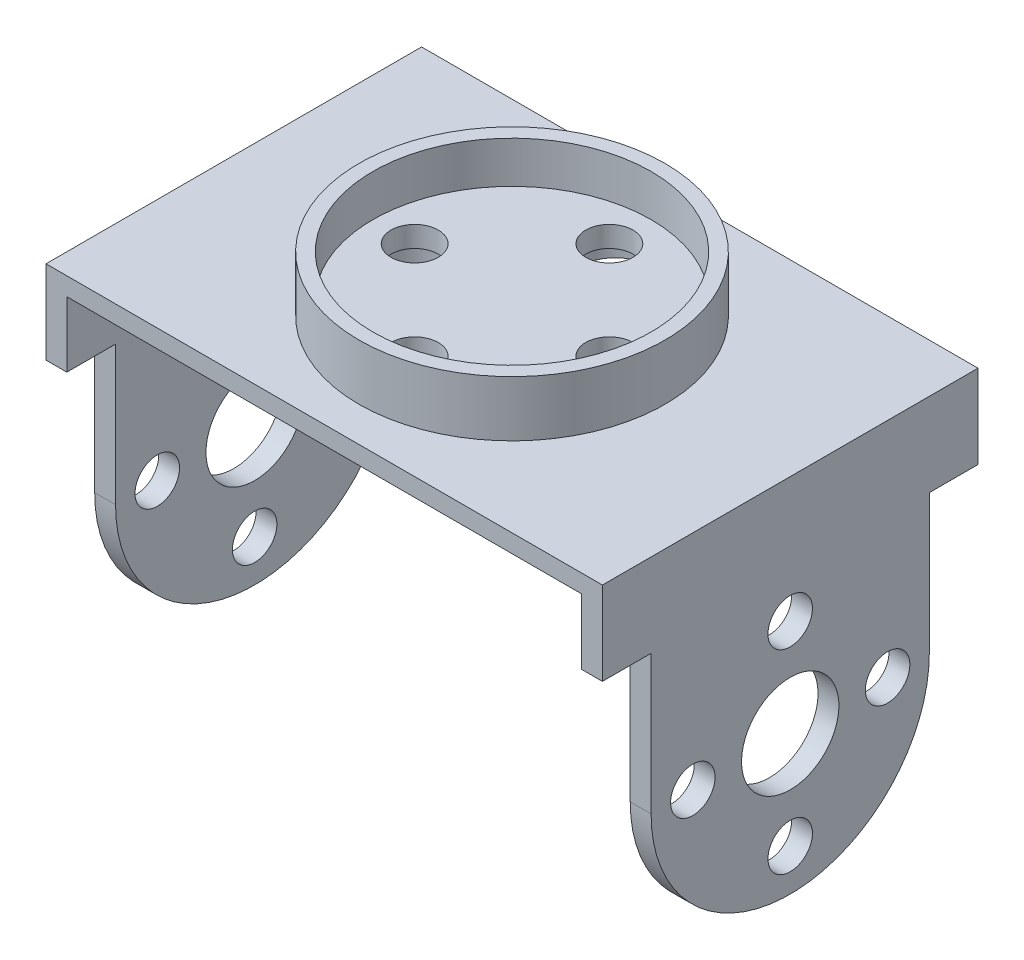
SolidWorks part; units mm, degrees
ref_plane "前视基准面" through (0, 0, 0) normal (0, 0, 1) x (1, 0, 0)
ref_plane "上视基准面" through (0, 0, 0) normal (0, 1, 0) x (1, 0, 0)
ref_plane "右视基准面" through (0, 0, 0) normal (1, 0, 0) x (0, 0, -1)
other "Configuration Table"
sketch "草图1" plane through (0, 0, 0) normal (0, 0, 1) x (1, 0, 0)
  line L1 (0, 0) -> (40, 0)
  line L2 (0, 0) -> (0, 28)
  line L3 (0, 28) -> (40, 28)
  line L4 (40, 0) -> (40, 28)
  dimension "D1" = 40
  dimension "D2" = 28
extrude "凸台-拉伸1" add sketch "草图1" along normal blind 27
sketch "草图2" plane through (0, 0, 0) normal (0, -1, 0) x (1, 0, 0)
  line L0 (20, 0) -> (20, 50000) construction
  line L1 (0, 0) -> (40, 0) construction
  line L2 (0, 27) -> (40, 27) construction
  line L3 (1.5, 0) -> (38.5, 0)
  line L4 (1.5, 0) -> (1.5, 27)
  line L5 (1.5, 27) -> (38.5, 27)
  line L6 (38.5, 0) -> (38.5, 27)
  point P4 (20, 0)
  point P9 (20, 0)
  dimension "D1" = 37
extrude "切除-拉伸1" cut sketch "草图2" against normal offset from surface (25 mm away) 3 up to face at (20, 28, 13.5)
sketch "草图3" plane through (0, 0, 0) normal (-1, 0, 0) x (0, 0, 1)
  line L0 (13.5, 0) -> (13.5, -50000) construction
  line L1 (27, 0) -> (0, 0) construction
  circle A0 centre (13.5, 12) radius 7 construction
  circle A1 centre (13.5, 5) radius 1.6
  circle A2 centre (13.5, 12) radius 3.5
  circle A3 centre (6.5, 12) radius 1.6
  circle A4 centre (20.5, 12) radius 1.6
  circle A5 centre (13.5, 19) radius 1.6
  point P4 (13.5, 0)
  dimension "D1" = 14
  dimension "D2" = 3.2
  dimension "D3" = 7
  dimension "D4" = 3.2
  dimension "D5" = 3.2
  dimension "D6" = 3.2
  dimension "D7" = 12
extrude "切除-拉伸2" cut sketch "草图3" against normal through all
sketch "草图4" plane through (0, 28, 0) normal (0, 1, 0) x (1, 0, 0)
  line L0 (0, -13.5) -> (50000, -13.5) construction
  line L1 (0, -27) -> (0, 0) construction
  line L2 (20, 0) -> (20, -50000) construction
  line L3 (40, 0) -> (0, 0) construction
  circle A0 centre (20, -13.5) radius 11
  circle A1 centre (20, -13.5) radius 10
  point P4 (0, -13.5)
  point P9 (20, 0)
  dimension "D1" = 22
  dimension "D2" = 20
extrude "凸台-拉伸2" add sketch "草图4" along normal blind 4 contours A0 A1
sketch "草图11" plane through (0, 28, 0) normal (0, 1, 0) x (1, 0, 0)
  circle A1 centre (20, -13.5) radius 10
  circle A2 centre (20, -13.5) radius 10
  dimension "D1" = 0
extrude "凸台-拉伸3" add sketch "草图11" along normal blind 1
sketch "草图6" plane through (0, 28, 0) normal (0, 1, 0) x (1, 0, 0)
  line L0 (38, -13.5) -> (-49962, -13.5) construction
  line L1 (40, -27) -> (40, 0) construction
  line L2 (20, 0) -> (20, -50000) construction
  line L3 (40, 0) -> (0, 0) construction
  circle A0 centre (20, -13.5) radius 7 construction
  circle A1 centre (20, -6.5) radius 1.7
  circle A2 centre (27, -13.5) radius 1.7
  circle A3 centre (20, -20.5) radius 1.7
  circle A4 centre (13, -13.5) radius 1.7
  point P4 (40, -13.5)
  point P9 (20, 0)
  dimension "D1" = 14
  dimension "D2" = 3.4
  dimension "D3" = 3.4
  dimension "D4" = 3.4
  dimension "D5" = 3.4
extrude "切除-拉伸3" cut sketch "草图6" against normal through all both and the other way through all
sketch "草图7" plane through (0, 25, 0) normal (0, -1, 0) x (1, 0, 0)
  circle A0 centre (20, 20.5) radius 2.8
  circle A1 centre (27, 13.5) radius 2.8
  circle A2 centre (20, 6.5) radius 2.8
  circle A3 centre (13, 13.5) radius 2.8
  dimension "D1" = 5.6
  dimension "D2" = 5.6
  dimension "D3" = 5.6
  dimension "D4" = 5.6
extrude "切除-拉伸4" cut sketch "草图7" against normal blind 2.5
sketch "草图10" plane through (1.5, 0, 0) normal (1, 0, 0) x (0, 0, -1)
  line L0 (0, 25) -> (-27, 25) construction
  line L1 (0, 25) -> (-27, 25)
  line L2 (0, 25) -> (0, 26.7)
  line L3 (0, 26.7) -> (-13.5, 25)
  line L4 (-13.5, 24.8773) -> (-13.5, -49975.1227) construction
  line L5 (-27, 26.7) -> (-13.5, 25)
  line L6 (-27, 25) -> (-27, 26.7)
  line M15 (0, 25) -> (-27, 25)
  dimension "D1" = 1.7
extrude "切除-拉伸6" cut sketch "草图10" along normal up to surface (37 mm away) contours L2 L3 M15 | L6 L1 L5 up to face at (38.5, 5, 11.9)
sketch "草图9" plane through (0, 0, 0) normal (-1, 0, 0) x (0, 0, 1)
  line L0 (0, 22) -> (27, 22)
  line L2 (3.5, 12) -> (3.5, 22)
  line L3 (23.5, 12) -> (23.5, 22)
  line L6 (0, 28) -> (0, 0)
  line L7 (0, 0) -> (27, 0)
  line L8 (27, 0) -> (27, 28)
  line L9 (27, 28) -> (0, 28)
  line L10 (0, 28) -> (0, 0)
  line L11 (0, 0) -> (27, 0)
  line L12 (27, 0) -> (27, 28)
  line L13 (27, 28) -> (0, 28)
  circle A0 centre (13.5, 12) radius 10
  dimension "D1" = 0
  dimension "D2" = 20
extrude "切除-拉伸5" cut sketch "草图9" against normal through all
